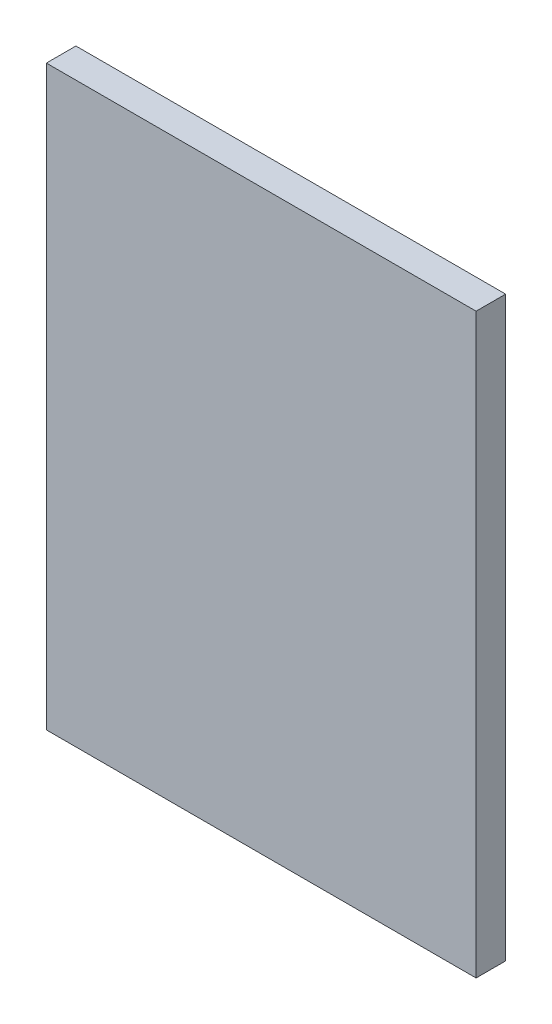
SolidWorks part; units mm, degrees
ref_plane "Front Plane" through (0, 0, 0) normal (0, 0, 1) x (1, 0, 0)
ref_plane "Top Plane" through (0, 0, 0) normal (0, 1, 0) x (1, 0, 0)
ref_plane "Right Plane" through (0, 0, 0) normal (1, 0, 0) x (0, 0, -1)
sketch "Sketch1" plane through (0, 0, 0) normal (0, 0, 1) x (1, 0, 0)
  line L1 (-17.45, -23.45) -> (17.45, -23.45)
  line L2 (-17.45, -23.45) -> (-17.45, 23.45)
  line L3 (-17.45, 23.45) -> (17.45, 23.45)
  line L4 (17.45, -23.45) -> (17.45, 23.45)
  line L5 (-17.45, -23.45) -> (17.45, 23.45) construction
  line L6 (-17.45, 23.45) -> (17.45, -23.45) construction
  point P0 (0, 0)
extrude "Envelope" add sketch "Sketch1" along normal blind 2.4
